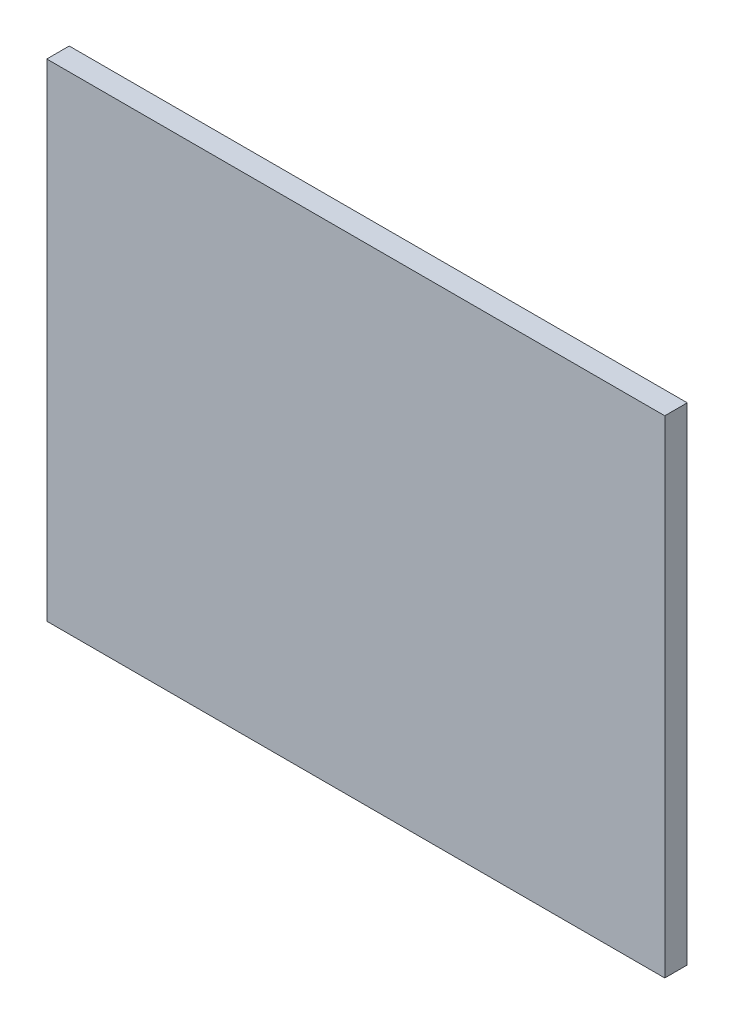
SolidWorks part; units mm, degrees
ref_plane "Front Plane" through (0, 0, 0) normal (0, 0, 1) x (1, 0, 0)
ref_plane "Top Plane" through (0, 0, 0) normal (0, 1, 0) x (1, 0, 0)
ref_plane "Right Plane" through (0, 0, 0) normal (1, 0, 0) x (0, 0, -1)
sketch "Sketch1" plane through (0, 0, 0) normal (0, 0, 1) x (1, 0, 0)
  line L0 (41.5035, -31.7394) -> (-40.9965, -31.7394)
  line L1 (41.5035, -31.7394) -> (41.5035, 33.2606)
  line L2 (41.5035, 33.2606) -> (-40.9965, 33.2606)
  line L3 (-40.9965, -31.7394) -> (-40.9965, 33.2606)
  line L4 (0, 59.8318) -> (0, -56.2825) construction
  line L5 (-61.0994, 0) -> (53.2402, 0) construction
  dimension "D1" = 65
  dimension "D2" = 82.5
extrude "Boss-Extrude1" add sketch "Sketch1" along normal mid plane 3
sketch "Sketch2" plane through (0, 0, -1.5) normal (0, 0, -1) x (-1, 0, 0)
  line L0 (-37.3212, -28.1056) -> (38.0015, -28.1056)
  line L1 (38.0015, -28.1056) -> (38.0015, 28.1002)
  line L2 (38.0015, 28.1002) -> (-37.3212, 28.1002)
  line L3 (-37.3212, 28.1002) -> (-37.3212, -28.1056)
  line L4 (-35.8212, -26.6056) -> (36.5015, -26.6056)
  line L5 (36.5015, -26.6056) -> (36.5015, 26.6002)
  line L6 (-35.8212, 26.6002) -> (-35.8212, -26.6056)
  line L7 (36.5015, 26.6002) -> (-35.8212, 26.6002)
extrude "Cut-Extrude1" cut sketch "Sketch2" against normal blind 1.5
